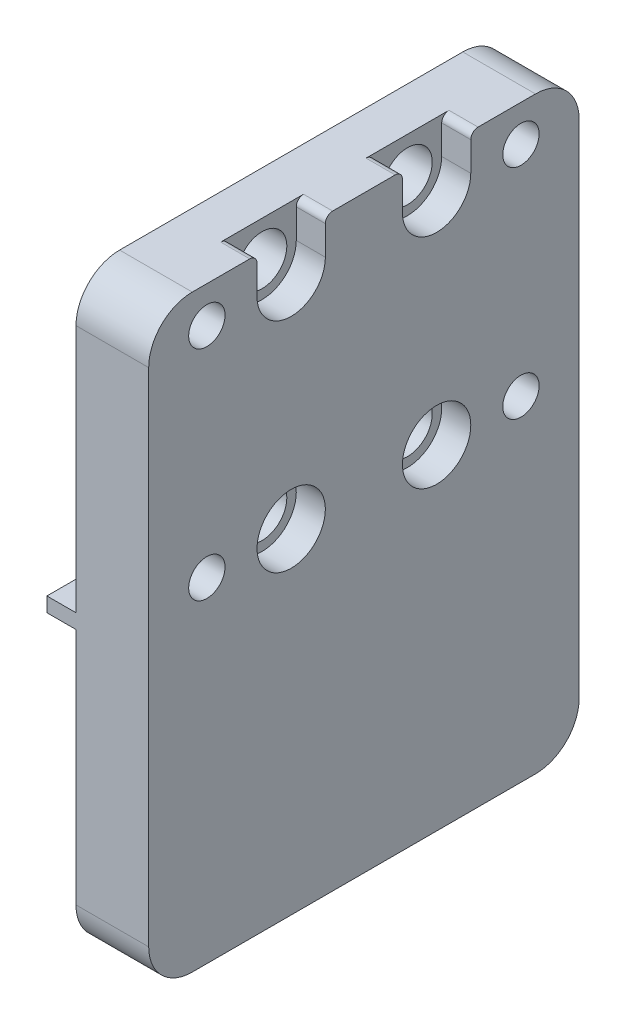
SolidWorks part; units mm, degrees
ref_plane "前视基准面" through (0, 0, 0) normal (0, 0, 1) x (1, 0, 0)
ref_plane "上视基准面" through (0, 0, 0) normal (0, 1, 0) x (1, 0, 0)
ref_plane "右视基准面" through (0, 0, 0) normal (1, 0, 0) x (0, 0, -1)
ref_plane "基准面1" through (-7, 0, 0) normal (-1, 0, 0) x (0, -1, 0)
sketch "草图1" plane through (-7, 0, 0) normal (-1, 0, 0) x (0, -1, 0)
  line L0 (3.1, 46.8114) -> (43.6, 46.8114)
  line L1 (43.6, 46.8114) -> (43.6, 76.4114)
  line L2 (43.6, 76.4114) -> (3.1, 76.4114)
  line L3 (3.1, 76.4114) -> (3.1, 46.8114)
extrude "凸台-拉伸1" add sketch "草图1" against normal blind 7
sketch "草图2" plane through (0, 0, 46.8114) normal (0, 0, -1) x (-1, 0, 0)
  line L0 (5, -3.1) -> (5, -23.2)
  line L1 (5, -23.2) -> (7, -23.2)
  line L2 (7, -23.2) -> (7, -3.1)
  line L3 (7, -3.1) -> (5, -3.1)
extrude "切除-拉伸1" cut sketch "草图2" against normal through all
sketch "草图3" plane through (0, 0, 46.8114) normal (0, 0, -1) x (-1, 0, 0)
  line L0 (7, -43.6) -> (7, -24.2)
  line L1 (7, -24.2) -> (5, -24.2)
  line L2 (5, -24.2) -> (5, -43.6)
  line L3 (5, -43.6) -> (7, -43.6)
extrude "切除-拉伸2" cut sketch "草图3" against normal through all
sketch "草图4" plane through (0, 0, 0) normal (1, 0, 0) x (0, 0, -1)
  line L0 (-58.9614, -3.1) -> (-58.9614, -5.6)
  line L1 (-54.2614, -5.6) -> (-54.2614, -3.1)
  line L2 (-54.2614, -3.1) -> (-58.9614, -3.1)
  arc A0 (-58.9614, -5.6) -> (-54.2614, -5.6) centre (-56.6114, -5.6) ccw
extrude "切除-拉伸3" cut sketch "草图4" against normal blind 2
sketch "草图5" plane through (0, 0, 0) normal (1, 0, 0) x (0, 0, -1)
  line L0 (-68.9614, -3.1) -> (-68.9614, -5.6)
  line L1 (-64.2614, -5.6) -> (-64.2614, -3.1)
  line L2 (-64.2614, -3.1) -> (-68.9614, -3.1)
  arc A0 (-68.9614, -5.6) -> (-64.2614, -5.6) centre (-66.6114, -5.6) ccw
extrude "切除-拉伸4" cut sketch "草图5" against normal blind 2
ref_plane "基准面2" through (0, -31.7, 0) normal (0, 1, 0) x (1, 0, 0)
sketch "草图6" plane through (0, -31.7, 0) normal (0, 1, 0) x (1, 0, 0)
  line L0 (-10, -57.1114) -> (-10, -61.6114)
  line L1 (-10, -61.6114) -> (-5, -61.6114)
  line L2 (-5, -61.6114) -> (-5, -53.8614)
  line L3 (-5, -53.8614) -> (-9, -53.8614)
  line L4 (-9, -53.8614) -> (-9, -57.1114)
  line L5 (-9, -57.1114) -> (-10, -57.1114)
  line L6 (-10, -61.6114) -> (-5, -61.6114) construction
revolve "旋转1" add sketch "草图6" angle 360 about L6
hole_wizard "Ø2.5 (2.5) 直径孔1" positions "草图8" profile "草图7" hole size "Ø2.5" standard "ANSI Metric"
sketch "草图8" plane through (-5, 0, 0) normal (-1, 0, 0) x (0, 0, 1)
  point P0 (72.4114, -5.6)
  point P1 (50.8114, -20.6)
  point P2 (72.4114, -20.6)
  point P3 (50.8114, -5.6)
sketch "草图7" plane through (-5, -5.6, 72.4114) normal (0, 1, 0) x (0, 0, 1)
  line L0 (0, 0) -> (0, 5)
  line L1 (0, 5) -> (1.25, 5)
  line L2 (1.25, 5) -> (1.25, 0)
  line L5 (1.25, 0) -> (0, 0)
  line L11 (0, -6.35) -> (0, 107.95) construction
  dimension "通孔孔直径" = 2.5
  dimension "通孔孔深度" = 5
hole_wizard "Ø3.4 (3.4) 直径孔1" positions "草图10" profile "草图9" hole size "Ø3.4" standard "ANSI Metric"
sketch "草图10" plane through (-2, 0, 0) normal (1, 0, 0) x (0, 0, -1)
  point P0 (-56.6114, -5.6)
  point P1 (-66.6114, -5.6)
sketch "草图9" plane through (-2, -5.6, 56.6114) normal (0, 1, 0) x (0, 0, -1)
  line L0 (0, 0) -> (0, 8)
  line L1 (0, 8) -> (1.7, 8)
  line L2 (1.7, 8) -> (1.7, 0)
  line L5 (1.7, 0) -> (0, 0)
  line L11 (0, -6.35) -> (0, 107.95) construction
  dimension "通孔孔直径" = 3.4
  dimension "通孔孔深度" = 8
hole_wizard "M3 六角头机械螺钉的柱形沉头孔1" positions "草图12" profile "草图11" counterbore size "M3" standard "ANSI Metric"
sketch "草图12" plane through (0, 0, 0) normal (1, 0, 0) x (0, 0, -1)
  point P0 (-56.6114, -20.6)
  point P1 (-66.6114, -20.6)
sketch "草图11" plane through (0, -20.6, 56.6114) normal (0, 1, 0) x (0, 0, -1)
  line L0 (0, 0) -> (0, 10)
  line L1 (0, 10) -> (1.7, 10)
  line L3 (1.7, 10) -> (1.7, 2)
  line L4 (1.7, 2) -> (2.35, 2)
  line L5 (2.35, 2) -> (2.35, 0)
  line L7 (2.35, 0) -> (0, 0)
  line L11 (0, -6.35) -> (0, 107.95) construction
  dimension "通孔孔直径" = 3.4
  dimension "通孔孔深度" = 10
  dimension "柱形沉头孔直径" = 4.7
  dimension "柱形沉头孔深度" = 2
hole_wizard "M3 六角头机械螺钉的柱形沉头孔2" positions "草图14" profile "草图13" counterbore size "M3" standard "ANSI Metric"
sketch "草图14" plane through (-10, 0, 0) normal (-1, 0, 0) x (0, 0, 1)
  point P0 (61.6114, -31.7)
sketch "草图13" plane through (-10, -31.7, 61.6114) normal (0, 1, 0) x (0, 0, 1)
  line L0 (0, 0) -> (0, 5)
  line L1 (0, 5) -> (1.65, 5)
  line L2 (1.65, 5) -> (1.65, 1)
  line L3 (1.65, 1) -> (3.05, 1)
  line L4 (3.05, 1) -> (3.05, 0)
  line L5 (3.05, 0) -> (0, 0)
  line L10 (0, 5) -> (-1.65, 5) construction
  line L11 (0, -6.35) -> (0, 107.95) construction
  dimension "孔直径" = 3.3
  dimension "孔深度" = 5
  dimension "柱形沉头孔直径" = 6.1
  dimension "柱形沉头孔深度" = 1
  dimension "导头角度" = 180
fillet "圆角1" radius 0.5 4 edges at (-1, -3.1, 58.9614) (-1, -3.1, 64.2614) (-1, -3.1, 68.9614) (-1, -3.1, 54.2614)
fillet "圆角2" radius 3 4 edges at (-2.5, -43.6, 46.8114) (-2.5, -43.6, 76.4114) (-2.5, -3.1, 46.8114) (-2.5, -3.1, 76.4114)
fillet "圆角3" radius 5 2 edges at (-6, -24.2, 63.564) (-6, -24.2, 59.6589)
